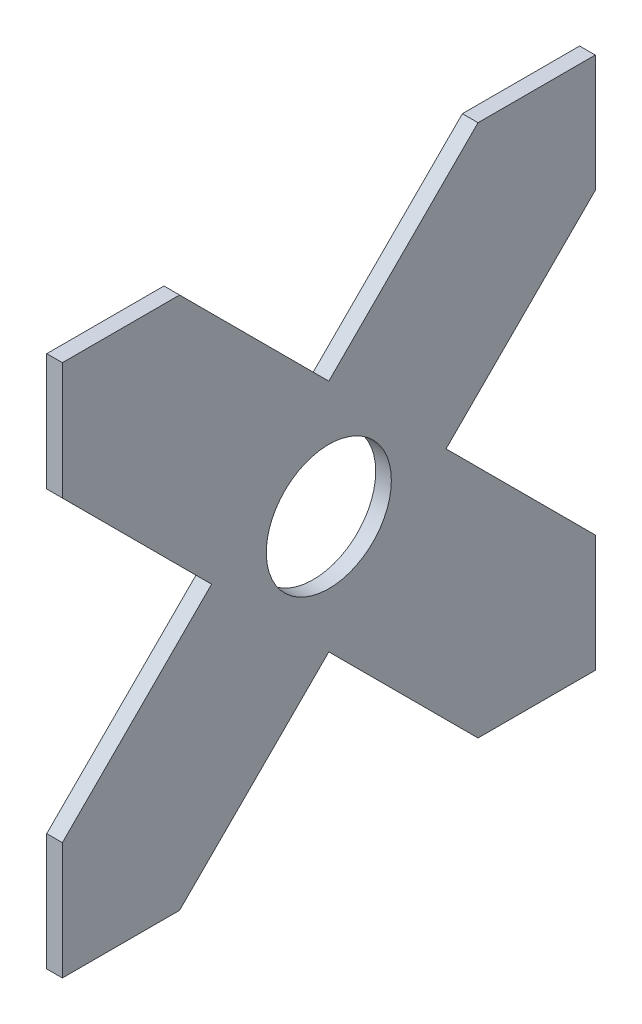
SolidWorks part; units mm, degrees
ref_plane "Front Plane" through (0, 0, 0) normal (0, 0, 1) x (1, 0, 0)
ref_plane "Top Plane" through (0, 0, 0) normal (0, 1, 0) x (1, 0, 0)
ref_plane "Right Plane" through (0, 0, 0) normal (1, 0, 0) x (0, 0, -1)
sketch "Sketch1" plane through (0, 0, 0) normal (1, 0, 0) x (0, 0, -1)
  line L0 (0, 0) -> (75, 0)
  line L1 (75, 0) -> (170.4594, 95.4594)
  line L2 (0, 0) -> (194.2866, 194.2866) construction
  line L3 (0, 75) -> (95.4594, 170.4594)
  line L4 (0, 0) -> (0, 75)
  line L5 (170.4594, 16.7561) -> (170.4594, 275.8556) construction
  line L6 (265.9188, 0) -> (170.4594, 95.4594)
  line L7 (340.9188, 0) -> (265.9188, 0)
  line L8 (340.9188, 0) -> (340.9188, 75)
  line L9 (340.9188, 75) -> (245.4594, 170.4594)
  line L10 (-29.0028, 170.4594) -> (386.1589, 170.4594) construction
  line L11 (170.4594, 324.1627) -> (170.4594, 65.0632) construction
  line L12 (0, 340.9188) -> (194.2866, 146.6322) construction
  line L13 (340.9188, 265.9188) -> (245.4594, 170.4594)
  line L14 (340.9188, 340.9188) -> (340.9188, 265.9188)
  line L15 (340.9188, 340.9188) -> (265.9188, 340.9188)
  line L16 (265.9188, 340.9188) -> (170.4594, 245.4594)
  line L17 (0, 340.9188) -> (0, 265.9188)
  line L18 (0, 265.9188) -> (95.4594, 170.4594)
  line L19 (75, 340.9188) -> (170.4594, 245.4594)
  line L20 (0, 340.9188) -> (75, 340.9188)
  dimension "D1" = 75
  dimension "D2" = 135
  dimension "D3" = 45
extrude "Boss-Extrude2" add sketch "Sketch1" along normal blind 10
sketch "Sketch3" plane through (10, 0, 0) normal (1, 0, 0) x (0, 0, -1)
  line L0 (3.7643, 170.4594) -> (380.6402, 170.4594) construction
  line L1 (170.4594, 95.4594) -> (170.4594, 245.4594) construction
  circle A0 centre (170.4594, 170.4594) radius 40
  circle A1 centre (170.4594, 170.4594) radius 60
  dimension "D1" = 80
  dimension "D2" = 120
extrude "Cut-Extrude1" cut sketch "Sketch3" against normal blind 10 contours A0
